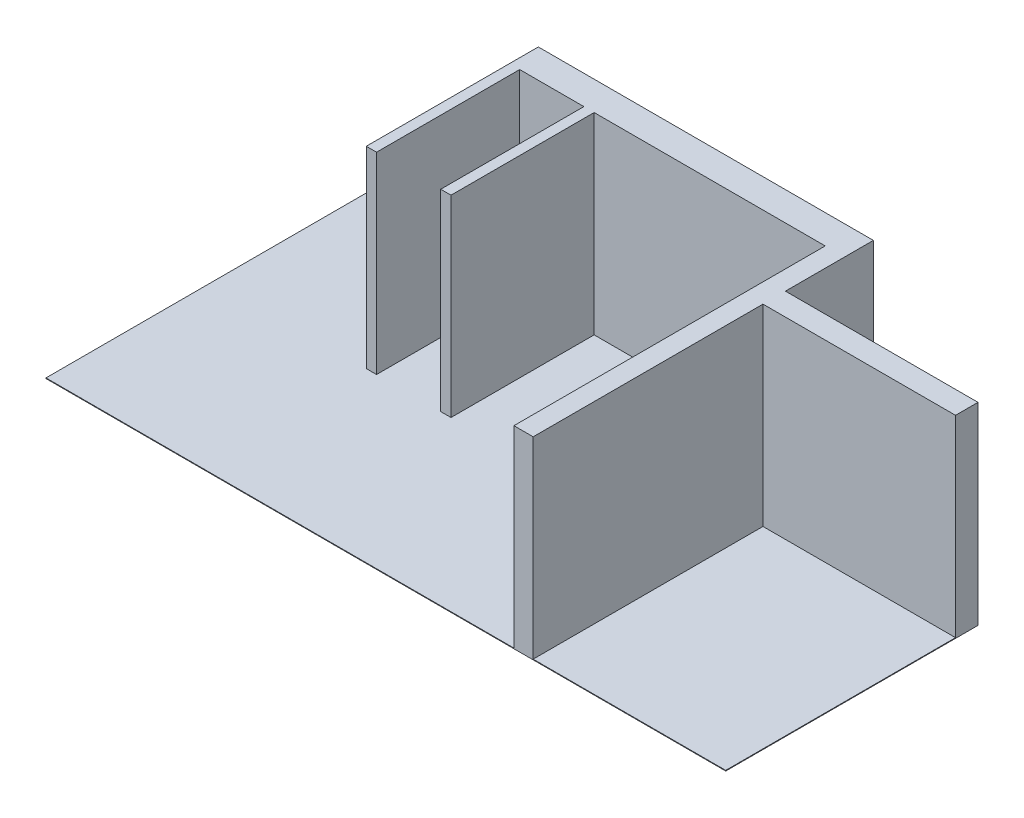
SolidWorks part; units mm, degrees
ref_plane "Płaszczyzna przednia" through (0, 0, 0) normal (0, 0, 1) x (1, 0, 0)
ref_plane "Płaszczyzna górna" through (0, 0, 0) normal (0, 1, 0) x (1, 0, 0)
ref_plane "Płaszczyzna prawa" through (0, 0, 0) normal (1, 0, 0) x (0, 0, -1)
sketch "Szkic1" plane through (0, 0, 0) normal (0, 1, 0) x (1, 0, 0)
  line L0 (-1800, 0) -> (1800, 0)
  line L1 (1800, 0) -> (1800, -4850)
  line L2 (1800, -4850) -> (2100, -4850)
  line L3 (2100, -4850) -> (2100, -1270)
  line L4 (2100, -1270) -> (5100, -1270)
  line L5 (5100, -1270) -> (5100, -920)
  line L6 (5100, -920) -> (2100, -920)
  line L7 (2100, -920) -> (2100, 450)
  line L8 (2100, 450) -> (-3120, 450)
  line L10 (-2960, 0) -> (-1960, 0)
  line L11 (-1960, 0) -> (-1960, -2230)
  line L12 (-1960, -2230) -> (-1800, -2230)
  line L13 (-1800, -2230) -> (-1800, 0)
  line L14 (-2960, 0) -> (-2960, -2230)
  line L15 (-2960, -2230) -> (-3120, -2230)
  line L16 (-3120, -2230) -> (-3120, 450)
  point P4 (0, 0)
  dimension "D1" = 450
  dimension "D2" = 160
  dimension "D3" = 350
  dimension "D4" = 1370
  dimension "D5" = 300
  dimension "D6" = 4850
  dimension "D7" = 3600
  dimension "D8" = 160
  dimension "D9" = 1000
  dimension "D10" = 3000
  dimension "D11" = 2230
extrude "Dodanie-wyciągnięcie1" add sketch "Szkic1" along normal blind 3000
sketch "Szkic3" plane through (0, 0, 0) normal (0, -1, 0) x (1, 0, 0)
  line L0 (-3120, -450) -> (-5489.7486, -450)
  line L1 (1800, 4850) -> (-5489.7486, 4850)
  line L2 (-5489.7486, 4850) -> (-5489.7486, -450)
  line L4 (2100, -450) -> (-3120, -450) construction
  line L5 (1800, -450) -> (-3120, -450)
  line L6 (1800, 4850) -> (1950, 4850)
  line L7 (1800, 4850) -> (2100, 4850) construction
  line L8 (1950, 4850) -> (1950, -450)
  line L9 (1950, -450) -> (1800, -450)
extrude "Dodanie-wyciągnięcie5" add sketch "Szkic3" along normal blind 10
sketch "Szkic4" plane through (0, 0, 0) normal (0, -1, 0) x (1, 0, 0)
  line L0 (1950, -450) -> (2100, -450)
  line L1 (2100, -450) -> (2100, 920)
  line L2 (2100, 920) -> (5100, 920)
  line L3 (5100, 920) -> (5100, 4850)
  line L7 (5100, 4850) -> (1950, 4850)
  line L8 (1950, 4850) -> (1950, -450)
extrude "Dodanie-wyciągnięcie6" add sketch "Szkic4" along normal blind 10
